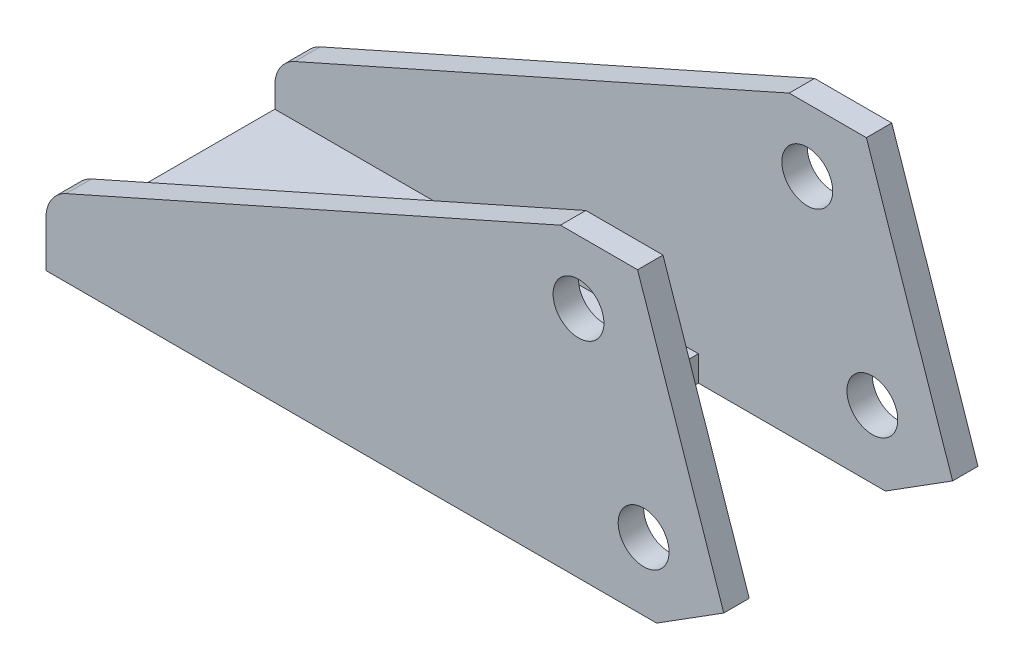
SolidWorks part; units mm, degrees
ref_plane "Спереди" through (0, 0, 0) normal (0, 0, 1) x (1, 0, 0)
ref_plane "Сверху" through (0, 0, 0) normal (0, 1, 0) x (1, 0, 0)
ref_plane "Справа" through (0, 0, 0) normal (1, 0, 0) x (0, 0, -1)
sketch "Эскиз1" plane through (0, 0, 0) normal (0, 0, 1) x (1, 0, 0)
  line L0 (1.1873, 4.528) -> (30.3559, 17.5)
  line L1 (0, 0) -> (36.035, 0)
  line L2 (0, 0) -> (0, 2.7006)
  line L5 (30.3559, 17.5) -> (34.9116, 17.5)
  line L6 (34.9116, 17.5) -> (40, 2.499)
  line L7 (40, 2.499) -> (36.035, 0)
  circle A0 centre (35.267, 4) radius 1.5
  circle A1 centre (31.4245, 13.7716) radius 1.5
  arc A2 (0, 2.7006) -> (1.1873, 4.528) centre (2, 2.7006) cw
  point P13 (0, 4)
  dimension "D4" = 10.5
  dimension "D5" = 4
  dimension "D6" = 4.5
  dimension "D7" = 4
  dimension "D8" = 2
  dimension "D1" = 40
  dimension "D2" = 4
  dimension "D3" = 17.5
extrude "Вытянуть1" add sketch "Эскиз1" along normal blind 15
sketch "Эскиз2" plane through (0, 0, 0) normal (0, -1, 0) x (1, 0, 0)
  line L0 (0, 15) -> (0, 0) construction
  line L1 (25, 13.5) -> (46.4981, 13.5)
  line L2 (25, 13.5) -> (25, 1.5)
  line L3 (25, 1.5) -> (46.4981, 1.5)
  line L4 (46.4981, 13.5) -> (46.4981, 1.5)
  line L5 (0, 15) -> (36.035, 15) construction
  line L6 (0, 0) -> (36.035, 0) construction
  dimension "D1" = 25
  dimension "D2" = 1.5
  dimension "D3" = 1.5
extrude "Вырез-Вытянуть1" cut sketch "Эскиз2" against normal blind 50
sketch "Эскиз3" plane through (25, 0, 0) normal (1, 0, 0) x (0, 0, -1)
  line L0 (-1.5, 15.1181) -> (-1.5, 0) construction
  line L1 (-13.5, 17.5) -> (-1.5, 17.5)
  line L2 (-13.5, 17.5) -> (-13.5, 1.5)
  line L3 (-13.5, 1.5) -> (-1.5, 1.5)
  line L4 (-1.5, 17.5) -> (-1.5, 1.5)
  line L5 (-13.5, 0) -> (-1.5, 0) construction
  dimension "D1" = 1.5
extrude "Вырез-Вытянуть2" cut sketch "Эскиз3" against normal blind 50
sketch "Эскиз4" plane through (0, 0, 0) normal (0, -1, 0) x (1, 0, 0)
  line L0 (0, 7.5) -> (25, 7.5) construction
  line L1 (0, 15) -> (0, 0) construction
  line L2 (25, 13.5) -> (25, 1.5) construction
  circle A0 centre (8, 7.5) radius 1.5
  circle A1 centre (20, 7.5) radius 1.5
  dimension "D1" = 12
  dimension "D2" = 8
  dimension "D3" = 3
  dimension "D4" = 3
extrude "Вырез-Вытянуть3" cut sketch "Эскиз4" against normal blind 50
